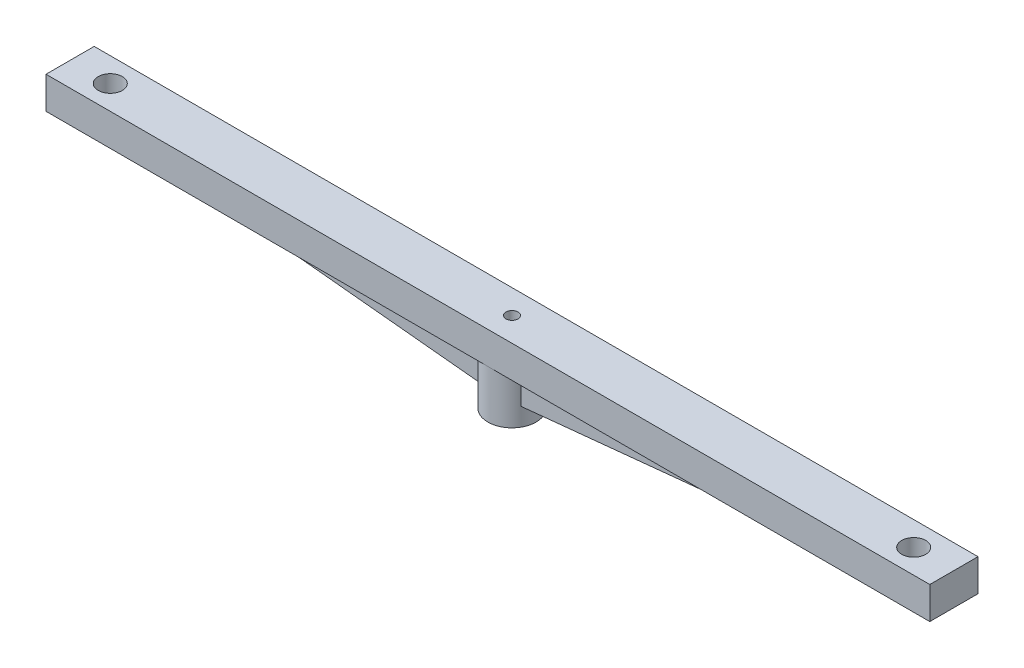
SolidWorks part; units mm, degrees
material "Plain Carbon Steel"
ref_plane "Front Plane" through (0, 0, 0) normal (0, 0, 1) x (1, 0, 0)
ref_plane "Top Plane" through (0, 0, 0) normal (0, 1, 0) x (1, 0, 0)
ref_plane "Right Plane" through (0, 0, 0) normal (1, 0, 0) x (0, 0, -1)
sketch "Sketch1" plane through (0, 0, 0) normal (0, 0, 1) x (1, 0, 0)
  line L1 (55, -2) -> (-55, -2)
  line L2 (55, -2) -> (55, 2)
  line L3 (55, 2) -> (-55, 2)
  line L4 (-55, -2) -> (-55, 2)
  line L5 (55, -2) -> (-55, 2) construction
  line L6 (55, 2) -> (-55, -2) construction
  point P0 (0, 0)
  dimension "D1" = 110
  dimension "D2" = 4
extrude "Boss-Extrude1" add sketch "Sketch1" along normal mid plane 6
sketch "Sketch2" plane through (0, 0, 0) normal (0, 0, 1) x (1, 0, 0)
  line L0 (-40, -2) -> (0, -6)
  line L1 (-55, -2) -> (55, -2) construction
  line L2 (0, -6) -> (40, -2)
  line L3 (0, -2) -> (0, -6) construction
  line L4 (-55, 2) -> (-55, -2) construction
  line L5 (-40, -2) -> (40, -2)
  dimension "D1" = 4
  dimension "D2" = 15
extrude "Boss-Extrude2" add sketch "Sketch2" along normal mid plane 3
hole_wizard "Ø3.0 (3) Diameter Hole1" positions "Sketch3" profile "Sketch4" hole size "Ø3.0" standard "ANSI Metric" end condition up to next
sketch "Sketch3" plane through (0, 2, 0) normal (0, 1, 0) x (1, 0, 0)
  line L0 (-55, -3) -> (-55, 3) construction
  line L1 (55, -3) -> (55, 3) construction
  point P0 (-50, 0)
  point P2 (50, 0)
  dimension "D1" = 5
  dimension "D2" = 5
sketch "Sketch4" plane through (-50, 2, 0) normal (1, 0, 0) x (0, 0, 1)
  line L0 (0, 0) -> (0, 4)
  line L1 (0, 4) -> (1.5, 4)
  line L2 (1.5, 4) -> (1.5, 0)
  line L5 (1.5, 0) -> (0, 0)
  line L11 (0, -6.35) -> (0, 107.95) construction
  dimension "Thru Hole Dia." = 3
  dimension "Thru Hole Depth" = 4
sketch "Sketch5" plane through (0, -2, 0) normal (0, -1, 0) x (1, 0, 0)
  line L0 (-55, 3) -> (55, 3) construction
  circle A0 centre (0, 0) radius 3
extrude "Boss-Extrude3" add sketch "Sketch5" along normal blind 6
hole_wizard "Ø1.5 (1.5) Diameter Hole1" positions "Sketch6" profile "Sketch7" hole size "Ø1.5" standard "ANSI Metric" end condition up to next
sketch "Sketch6" plane through (0, -8, 0) normal (0, -1, 0) x (-1, 0, 0)
  point P0 (0, 0)
sketch "Sketch7" plane through (0, -8, 0) normal (1, 0, 0) x (0, 0, -1)
  line L0 (0, 0) -> (0, 10)
  line L1 (0, 10) -> (0.75, 10)
  line L2 (0.75, 10) -> (0.75, 0)
  line L5 (0.75, 0) -> (0, 0)
  line L11 (0, -6.35) -> (0, 107.95) construction
  dimension "Thru Hole Dia." = 1.5
  dimension "Thru Hole Depth" = 10
sketch "Sketch8" plane through (0, -8, 0) normal (0, -1, 0) x (1, 0, 0)
  circle A0 centre (0, 0) radius 2
  dimension "D1" = 4
extrude "Cut-Extrude1" cut sketch "Sketch8" against normal up to surface (6 mm away) up to face at (-24.4498, -2, 0)
